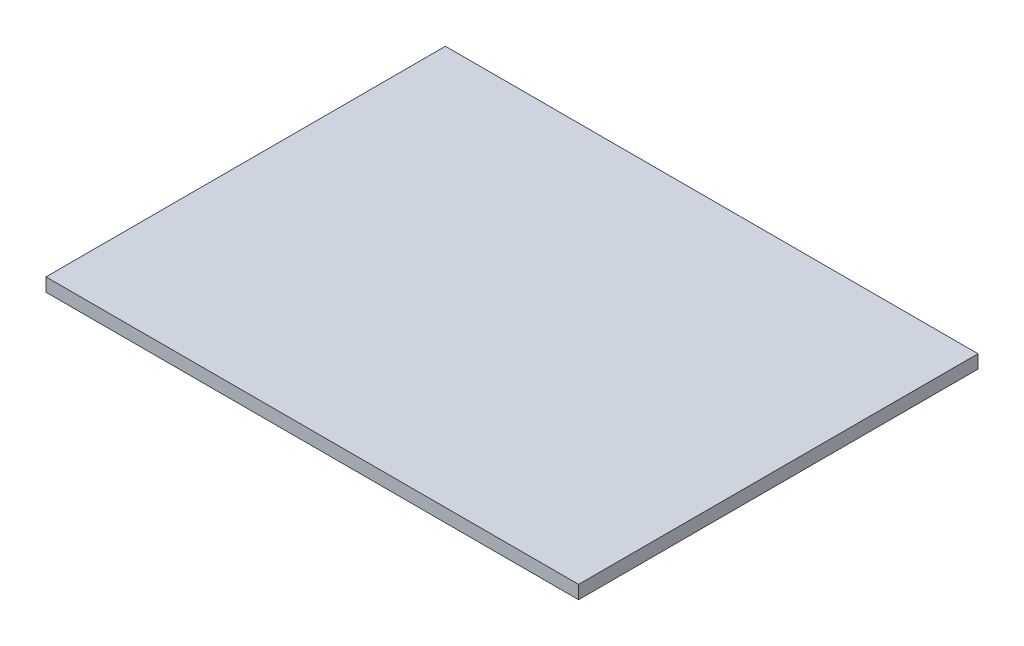
SolidWorks part; units mm, degrees
ref_plane "Front Plane" through (0, 0, 0) normal (0, 0, 1) x (1, 0, 0)
ref_plane "Top Plane" through (0, 0, 0) normal (0, 1, 0) x (1, 0, 0)
ref_plane "Right Plane" through (0, 0, 0) normal (1, 0, 0) x (0, 0, -1)
sketch "Sketch1" plane through (0, 0, 0) normal (0, 1, 0) x (1, 0, 0)
  line L0 (-254, 190.5) -> (254, -190.5) construction
  line L1 (-254, 190.5) -> (254, 190.5)
  line L2 (-254, 190.5) -> (-254, -190.5)
  line L3 (-254, -190.5) -> (254, -190.5)
  line L4 (254, 190.5) -> (254, -190.5)
  dimension "D1" = 508
  dimension "D2" = 381
extrude "Boss-Extrude1" add sketch "Sketch1" along normal blind 12.7
sketch "Sketch2" plane through (0, 12.7, 0) normal (0, 1, 0) x (1, 0, 0)
  line L0 (-254, 190.5) -> (-254, -190.5) construction
  line L1 (-254, -190.5) -> (254, -190.5) construction
  spline S0 degree 3 poles (-254, -133.682) (32.77, -239.8394) (-387.8311, 38.3382) (-10.7374, 221.7436) (-156.3458, -3.629) (28.6435, -229.4609) (-55.1735, 264.9097) (425.7785, 116.9711) (68.0543, -190.5) knots 0 0 0 0 0.251762 0.349742 0.465327 0.568047 0.707177 1 1 1 1
